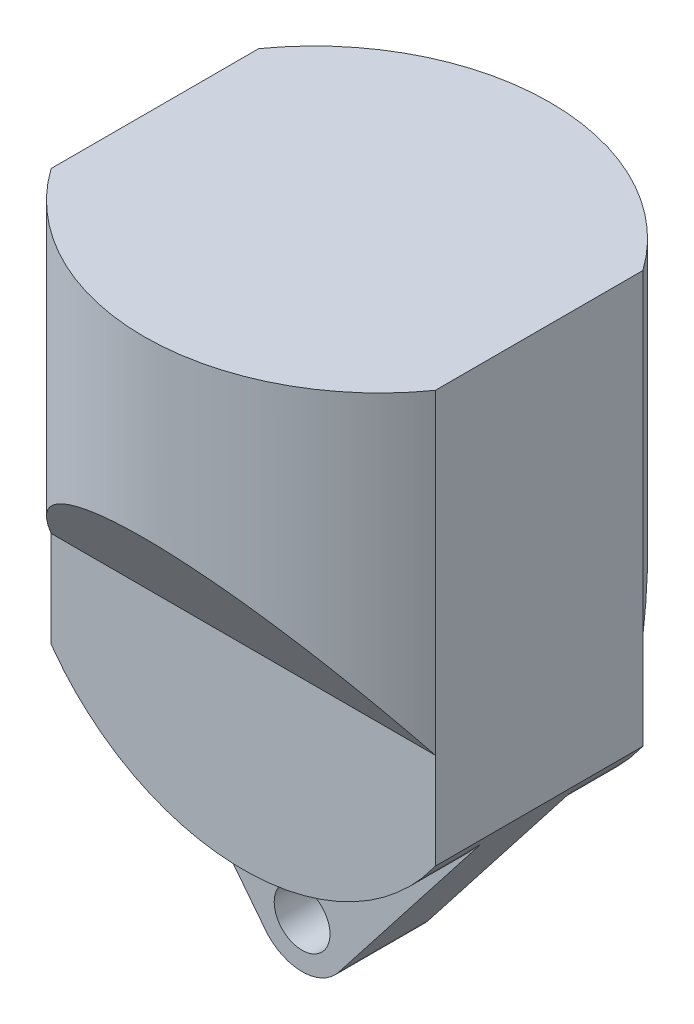
SolidWorks part; units mm, degrees
other "Детальный элемент1"
material "3.3320 (EN-AW 5019)"
ref_plane "Спереди" through (0, 0, 0) normal (0, 0, 1) x (1, 0, 0)
ref_plane "Сверху" through (0, 0, 0) normal (0, 1, 0) x (1, 0, 0)
ref_plane "Справа" through (0, 0, 0) normal (1, 0, 0) x (0, 0, -1)
sketch "Эскиз1" plane through (0, 0, 0) normal (0, 0, 1) x (1, 0, 0)
  line L0 (-62, 55) -> (-62, 188)
  line L1 (-62, 188) -> (62, 188)
  line L2 (62, 188) -> (62, 55)
  line L3 (62, 55) -> (12.048, -8.9357)
  line L4 (-62, 55) -> (-12.048, -8.9357)
  line L5 (0, -15) -> (43.0046, -15) construction
  arc A0 (-12.048, -8.9357) -> (12.048, -8.9357) centre (0, 0) ccw
  point P2 (0, 188)
  point P9 (-147.0566, 98.5968)
  dimension "D6" = 70
  dimension "D1" = 55
  dimension "D2" = 133
  dimension "D3" = 38
  dimension "D4" = 38
  dimension "D5" = 124
extrude "Бобышка-Вытянуть1" add sketch "Эскиз1" along normal blind 67
sketch "Эскиз2" plane through (0, 0, 67) normal (0, 0, 1) x (1, 0, 0)
  line L0 (0, 23) -> (0, 94.2763) construction
  line L1 (-62, 55) -> (-62, 188)
  line L2 (-62, 188) -> (62, 188)
  line L3 (62, 188) -> (62, 55)
  arc A0 (-62, 55) -> (62, 55) centre (0, 99.0625) ccw
  point P10 (0, 23)
  dimension "D1" = 32
  dimension "D2" = 76.0625
extrude "Вырез-Вытянуть1" cut sketch "Эскиз2" against normal blind 19 flip side to cut contours L1 L2 L3 A0
sketch "Эскиз4" plane through (0, 0, 0) normal (0, 0, -1) x (-1, 0, 0)
  line L0 (0, 23) -> (0, 80.2138) construction
  line L1 (-62, 55) -> (-62, 188)
  line L2 (-62, 188) -> (62, 188)
  line L3 (62, 188) -> (62, 55)
  arc A0 (-62, 55) -> (62, 55) centre (0, 99.0625) ccw
  point P5 (0, 23)
  dimension "D1" = 32
extrude "Вырез-Вытянуть2" cut sketch "Эскиз4" against normal blind 19 flip side to cut
sketch "Эскиз5" plane through (0, 188, 0) normal (0, 1, 0) x (1, 0, 0)
  line L0 (0, 0) -> (0, 32) construction
  line L1 (0, -67) -> (0, -99) construction
  line L2 (62, -67) -> (-62, -67) construction
  line L3 (-62, 0) -> (62, 0)
  line L4 (-62, -67) -> (62, -67)
  arc A0 (-62, 0) -> (62, 0) centre (0, -44.0625) cw
  arc A1 (-62, -67) -> (62, -67) centre (0, -22.9375) ccw
  point P10 (0, 32)
  point P16 (0, -99)
  dimension "D1" = 32
  dimension "D2" = 32
extrude "Бобышка-Вытянуть2" add sketch "Эскиз5" against normal blind 102
sketch "Эскиз6" plane through (62, 0, 0) normal (1, 0, 0) x (0, 0, -1)
  line L0 (0, 86) -> (32, 131.7007)
  line L1 (32, 86) -> (32, 188) construction
  line L2 (32, 131.7007) -> (32, 86)
  line L3 (0, 86) -> (32, 86) construction
  line L4 (32, 86) -> (0, 86)
  line L5 (-67, 86) -> (-99, 131.7007)
  line L6 (-99, 131.7007) -> (-99, 86)
  line L7 (-99, 86) -> (-67, 86)
  line L8 (-67, 55) -> (-67, 86) construction
  line L10 (0, 55) -> (0, 86) construction
  dimension "D1" = 145
  dimension "D2" = 145
extrude "Вырез-Вытянуть3" cut sketch "Эскиз6" against normal through all
sketch "Эскиз7" plane through (0, 0, 19) normal (0, 0, -1) x (-1, 0, 0)
  circle A0 centre (0, 0) radius 9
extrude "Вырез-Вытянуть4" cut sketch "Эскиз7" against normal through all
